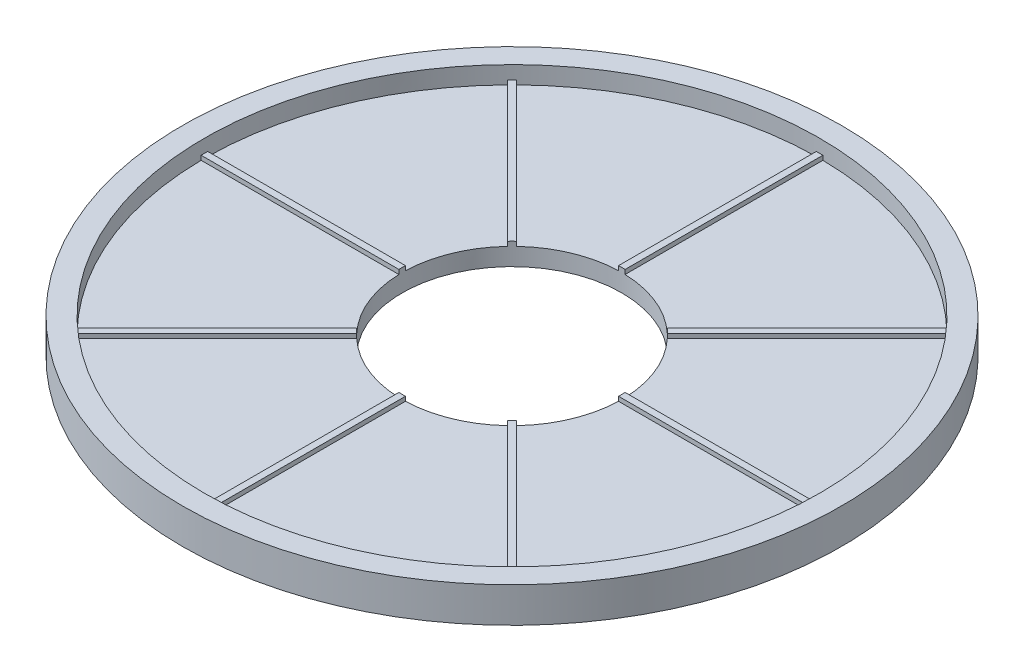
SolidWorks part; units mm, degrees
ref_plane "Alzado" through (0, 0, 0) normal (0, 0, 1) x (1, 0, 0)
ref_plane "Planta" through (0, 0, 0) normal (0, 1, 0) x (1, 0, 0)
ref_plane "Vista lateral" through (0, 0, 0) normal (1, 0, 0) x (0, 0, -1)
sketch "Croquis1" plane through (0, 0, 0) normal (0, 1, 0) x (1, 0, 0)
  circle A0 centre (0, 0) radius 75
  dimension "D1" = 150
extrude "Saliente-Extruir1" add sketch "Croquis1" along normal blind 4
sketch "Croquis3" plane through (0, 4, 0) normal (0, 1, 0) x (1, 0, 0)
  line L0 (-70, 0) -> (70, 0) construction
  line L1 (0, -70) -> (0, 70) construction
  line L3 (-49.4975, -49.4975) -> (49.4975, 49.4975) construction
  line L5 (-49.4975, 49.4975) -> (49.4975, -49.4975) construction
  circle A0 centre (0, 0) radius 75
  circle A1 centre (0, 0) radius 70
  dimension "D1" = 150
  dimension "D2" = 5
extrude "Saliente-Extruir2" add sketch "Croquis3" along normal blind 4
sketch "Croquis7" plane through (0, 4, 0) normal (0, 1, 0) x (1, 0, 0)
  line L0 (51.6188, -52.6795) -> (52.6795, -51.6188)
  line L9 (73.75, -0.75) -> (-73.75, -0.75)
  line L10 (73.75, -0.75) -> (73.75, 0.75)
  line L11 (73.75, 0.75) -> (-73.75, 0.75)
  line L12 (-73.75, -0.75) -> (-73.75, 0.75)
  line L13 (73.75, -0.75) -> (-73.75, 0.75) construction
  line L14 (73.75, 0.75) -> (-73.75, -0.75) construction
  line L15 (51.6188, -52.6795) -> (-52.6795, 51.6188)
  line L16 (-52.6795, 51.6188) -> (-51.6188, 52.6795)
  line L17 (52.6795, -51.6188) -> (-51.6188, 52.6795)
  line L18 (-0.75, -73.75) -> (0.75, -73.75)
  line L19 (-0.75, -73.75) -> (-0.75, 73.75)
  line L20 (-0.75, 73.75) -> (0.75, 73.75)
  line L21 (0.75, -73.75) -> (0.75, 73.75)
  line L22 (-52.6795, -51.6188) -> (-51.6188, -52.6795)
  line L23 (-52.6795, -51.6188) -> (51.6188, 52.6795)
  line L24 (51.6188, 52.6795) -> (52.6795, 51.6188)
  line L25 (-51.6188, -52.6795) -> (52.6795, 51.6188)
  line L26 (-73.75, 0.75) -> (-73.75, -0.75)
  line L27 (-73.75, 0.75) -> (73.75, 0.75)
  line L28 (73.75, 0.75) -> (73.75, -0.75)
  line L29 (-73.75, -0.75) -> (73.75, -0.75)
  point P0 (0, 0)
  point P25 (0, 0)
  dimension "D1" = 1.5
  dimension "D2" = 147.5
  dimension "D3" = 5
sketch "Croquis2" plane through (0, 0, 0) normal (0, -1, 0) x (1, 0, 0)
  line L0 (0, 0) -> (-75, 0) construction
  circle A0 centre (0, 0) radius 75 construction
  circle A1 centre (-60, 0) radius 2.5
  circle A2 centre (-42.4264, 42.4264) radius 2.5
  circle A3 centre (0, 60) radius 2.5
  circle A4 centre (42.4264, 42.4264) radius 2.5
  circle A5 centre (60, 0) radius 2.5
  circle A6 centre (42.4264, -42.4264) radius 2.5
  circle A7 centre (0, -60) radius 2.5
  circle A8 centre (-42.4264, -42.4264) radius 2.5
  point P25 (0, 0)
  dimension "D1" = 5
  dimension "D2" = 60
  dimension "D3" = 8
extrude "Saliente-Extruir3" add sketch "Croquis7" along normal blind 1 contours L11 L19 L17 L15 | L23 L24 L25 L22
extrude "Cortar-Extruir1" cut sketch "Croquis2" against normal blind 2
sketch "Croquis4" plane through (0, 0, 0) normal (0, -1, 0) x (1, 0, 0)
  circle A0 centre (0, 0) radius 25
  dimension "D1" = 50
extrude "Cortar-Extruir2" cut sketch "Croquis4" against normal blind 6
